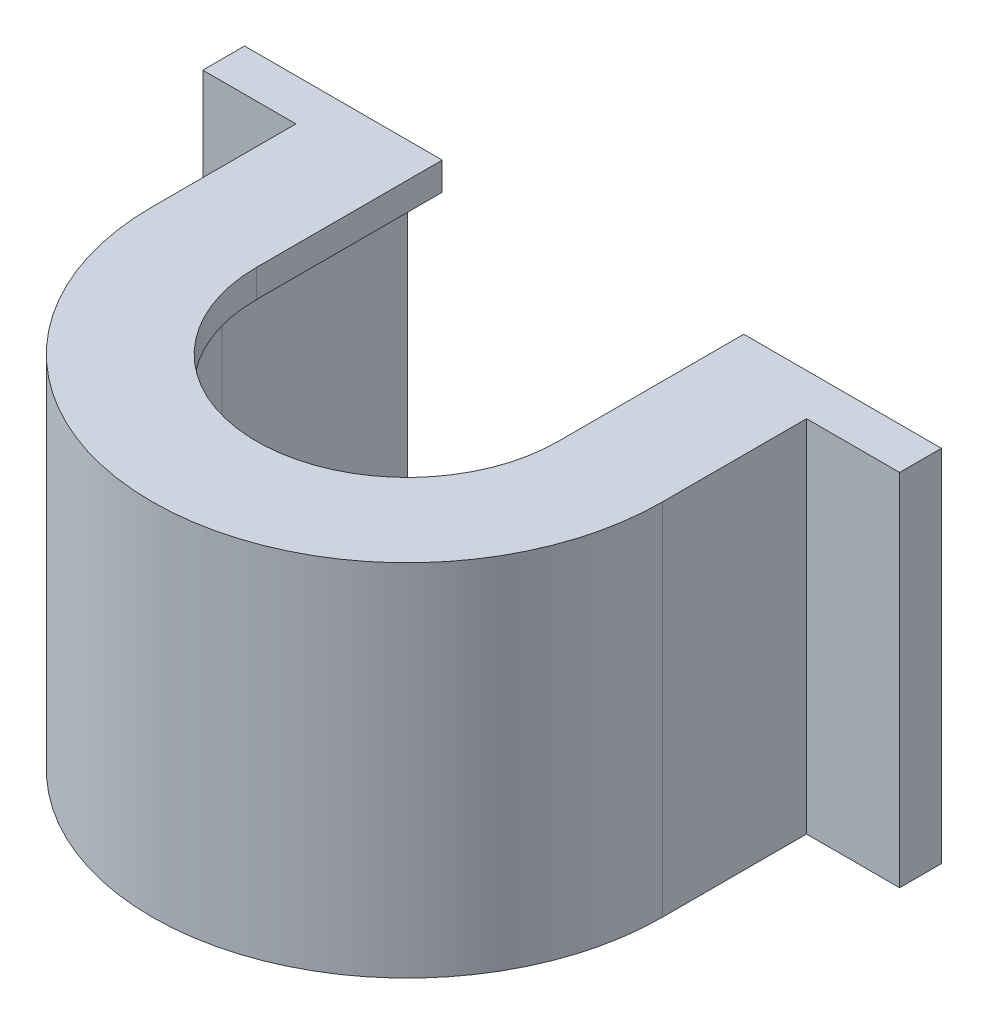
SolidWorks part; units mm, degrees
ref_plane "Front Plane" through (0, 0, 0) normal (0, 0, 1) x (1, 0, 0)
ref_plane "Top Plane" through (0, 0, 0) normal (0, 1, 0) x (1, 0, 0)
ref_plane "Right Plane" through (0, 0, 0) normal (1, 0, 0) x (0, 0, -1)
sketch "Sketch1" plane through (0, 0, 0) normal (0, 1, 0) x (1, 0, 0)
  line L0 (-13.32, 0) -> (-13.32, 13.32)
  line L1 (-13.32, 13.32) -> (-25, 13.32)
  line L2 (-25, 13.32) -> (-25, 10.32)
  line L3 (-25, 10.32) -> (-18.32, 10.32)
  line L4 (-18.32, 10.32) -> (-18.32, 2.0756)
  line L5 (13.32, 0) -> (13.32, 13.32)
  line L6 (13.32, 13.32) -> (25, 13.32)
  line L7 (25, 13.32) -> (25, 10.32)
  line L8 (25, 10.32) -> (18.32, 10.32)
  line L9 (18.32, 10.32) -> (18.32, 1.6853)
  line L10 (-18.32, 2.0756) -> (-18.32, 2.0756)
  line L11 (-18.32, 2.0756) -> (-18.32, 2.0756)
  line L12 (-18.32, 2.0756) -> (-18.32, 2.0756)
  line L13 (-18.32, 2.0756) -> (-18.32, 2.0756)
  line L14 (-18.32, 0) -> (-18.32, 2.0756)
  line L15 (18.32, 0) -> (18.32, 1.6853)
  line L16 (18.32, 1.6853) -> (18.32, 1.6853)
  line L17 (18.32, 1.6853) -> (18.32, 1.6853)
  line L18 (18.32, 1.6853) -> (18.32, 1.6853)
  line L19 (18.32, 1.6853) -> (18.32, 1.6853)
  line L20 (18.32, 10.32) -> (18.32, 6.6853) construction
  line L21 (-18.32, 10.32) -> (-18.32, 7.0756) construction
  line L22 (0, 0) -> (0, 16.091) construction
  arc A0 (-13.32, 0) -> (13.32, 0) centre (0, 0) ccw
  arc A1 (-18.32, 0) -> (18.32, 0) centre (0, 0) ccw
  point P14 (0, -13.32)
  dimension "D1" = 13.32
  dimension "D2" = 26.64
  dimension "D4" = 50
  dimension "D5" = 3
  dimension "D6" = 3
  dimension "D3" = 5
extrude "Boss-Extrude1" add sketch "Sketch1" along normal blind 20 contours L14 A1 L15 L9 L8 L7 L6 L5 A0 L0 L1 L2 L3 L4
sketch "Sketch2" plane through (0, 20, 0) normal (0, 1, 0) x (1, 0, 0)
  line L10 (-18.32, 10.32) -> (-18.32, 0)
  line L11 (18.32, 0) -> (18.32, 10.32)
  line L12 (18.32, 10.32) -> (25, 10.32)
  line L13 (25, 10.32) -> (25, 13.32)
  line L14 (25, 13.32) -> (13.32, 13.32)
  line L15 (13.32, 13.32) -> (13.32, 0)
  line L16 (-13.32, 0) -> (-13.32, 13.32)
  line L17 (-13.32, 13.32) -> (-25, 13.32)
  line L18 (-25, 13.32) -> (-25, 10.32)
  line L19 (-25, 10.32) -> (-18.32, 10.32)
  line L20 (-18.32, 10.32) -> (-18.32, 0)
  line L21 (18.32, 0) -> (18.32, 10.32)
  line L22 (18.32, 10.32) -> (25, 10.32)
  line L23 (25, 10.32) -> (25, 13.32)
  line L24 (25, 13.32) -> (13.32, 13.32)
  line L25 (13.32, 13.32) -> (13.32, 0)
  line L26 (-13.32, 0) -> (-13.32, 13.32)
  line L27 (-13.32, 13.32) -> (-25, 13.32)
  line L28 (-25, 13.32) -> (-25, 10.32)
  line L29 (-25, 10.32) -> (-18.32, 10.32)
  arc A2 (-18.32, 0) -> (18.32, 0) centre (0, 0) ccw
  arc A3 (-13.32, 0) -> (13.32, 0) centre (0, 0) ccw
  arc A4 (-18.32, 0) -> (18.32, 0) centre (0, 0) ccw
  arc A5 (-13.32, 0) -> (13.32, 0) centre (0, 0) ccw
  dimension "D1" = 0
extrude "Boss-Extrude2" add sketch "Sketch2" along normal blind 12.7
sketch "Sketch3" plane through (0, 32.7, 0) normal (0, 1, 0) x (1, 0, 0)
  line L0 (-25, 13.32) -> (-10.82, 13.32)
  line L1 (25, 13.32) -> (10.82, 13.32)
  line L2 (-10.82, 5.82) -> (-10.82, 0) construction
  line L3 (-10.82, 5.82) -> (-10.82, 5.82)
  line L4 (-10.82, 5.82) -> (-10.82, 5.82)
  line L5 (-10.82, 13.32) -> (-10.82, 0)
  line L6 (10.82, 0) -> (10.82, 13.32)
  line L7 (10.82, 5.82) -> (10.82, 5.82)
  line L8 (10.82, 5.82) -> (10.82, 5.82)
  line L9 (10.82, 0) -> (10.82, 5.82) construction
  line L10 (-25, 10.32) -> (-18.32, 10.32)
  line L11 (-18.32, 10.32) -> (-18.32, 0)
  line L12 (18.32, 0) -> (18.32, 10.32)
  line L13 (18.32, 10.32) -> (25, 10.32)
  line L14 (25, 10.32) -> (25, 13.32)
  line L15 (25, 13.32) -> (13.32, 13.32)
  line L16 (13.32, 13.32) -> (13.32, 0)
  line L17 (-13.32, 0) -> (-13.32, 13.32)
  line L18 (-13.32, 13.32) -> (-25, 13.32)
  line L19 (-25, 13.32) -> (-25, 10.32)
  line L20 (-25, 10.32) -> (-18.32, 10.32)
  line L21 (-18.32, 10.32) -> (-18.32, 0)
  line L22 (18.32, 0) -> (18.32, 10.32)
  line L23 (18.32, 10.32) -> (25, 10.32)
  line L24 (25, 10.32) -> (25, 13.32)
  line L29 (-25, 13.32) -> (-25, 10.32)
  line L30 (-10.82, 5.82) -> (-9.4483, 5.82) construction
  line L31 (10.82, 5.82) -> (9.177, 5.82) construction
  line L32 (-25, 13.32) -> (-9.4483, 13.32) construction
  line L33 (25, 13.32) -> (9.177, 13.32) construction
  arc A0 (-10.82, 0) -> (10.82, 0) centre (0, 0) ccw
  arc A2 (-18.32, 0) -> (18.32, 0) centre (0, 0) ccw
  arc A3 (-13.32, 0) -> (13.32, 0) centre (0, 0) ccw
  arc A4 (-18.32, 0) -> (18.32, 0) centre (0, 0) ccw
  line M18 (-25, 10.32) -> (-18.32, 10.32)
  line M19 (-18.32, 10.32) -> (-18.32, 0)
  arc M20 (-18.32, 0) -> (18.32, 0) centre (0, 0) ccw
  line M21 (18.32, 0) -> (18.32, 10.32)
  line M22 (18.32, 10.32) -> (25, 10.32)
  line M23 (25, 10.32) -> (25, 13.32)
  line M24 (25, 13.32) -> (13.32, 13.32)
  line M25 (13.32, 13.32) -> (13.32, 0)
  arc M26 (13.32, 0) -> (-13.32, 0) centre (0, 0) cw
  line M27 (-13.32, 0) -> (-13.32, 13.32)
  line M28 (-13.32, 13.32) -> (-25, 13.32)
  line M29 (-25, 13.32) -> (-25, 10.32)
  dimension "D1" = 0
  dimension "D2" = 7.5
extrude "Boss-Extrude3" add sketch "Sketch3" along normal blind 2 contours A0 L5 L0 L1 L6 M27 M26 M25 | M29 M18 M19 M20 M21 M22 M23 M24 M25 M26 M27 M28
sketch "Sketch4" plane through (0, 0, 0) normal (0, 0, 1) x (1, 0, 0)
  line L0 (-25, 34.7) -> (-25, 0) construction
  line L1 (-25, 8.89) -> (27.3575, 8.89)
  line L2 (-25, 8.89) -> (-25, 0)
  line L3 (-25, 0) -> (27.3575, 0)
  line L4 (27.3575, 8.89) -> (27.3575, 0)
  point P6 (27.3575, 0)
  dimension "D1" = 8.89
extrude "Cut-Extrude1" cut sketch "Sketch4" against normal mid plane 44
